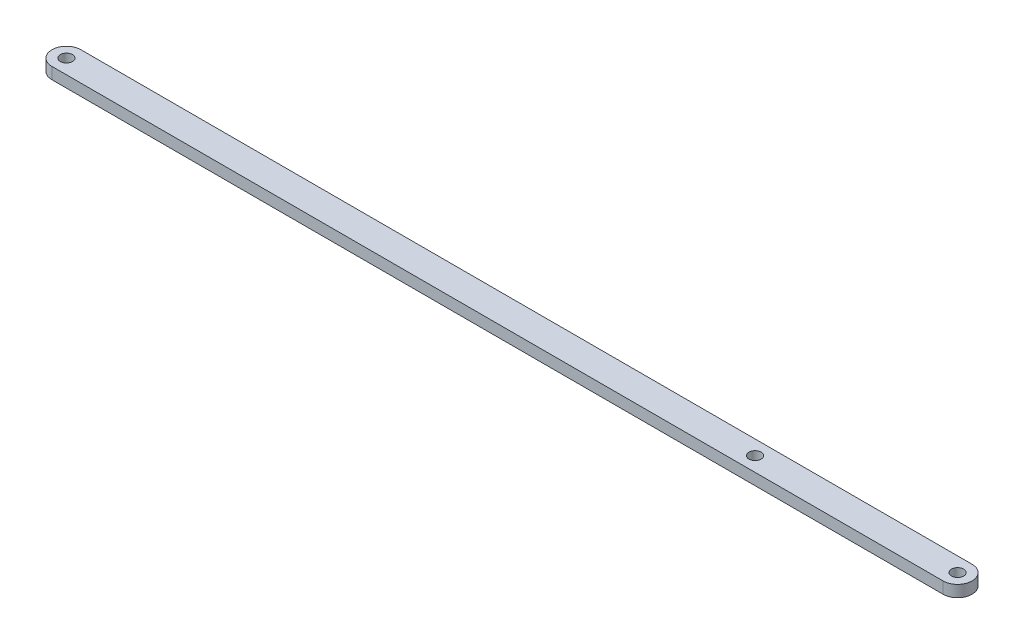
SolidWorks part; units mm, degrees
ref_plane "Front Plane" through (0, 0, 0) normal (0, 0, 1) x (1, 0, 0)
ref_plane "Top Plane" through (0, 0, 0) normal (0, 1, 0) x (1, 0, 0)
ref_plane "Right Plane" through (0, 0, 0) normal (1, 0, 0) x (0, 0, -1)
sketch "Sketch1" plane through (0, 0, 0) normal (0, 1, 0) x (1, 0, 0)
  line L0 (0, 0) -> (154, 0) construction
  line L1 (0, 2.5) -> (154, 2.5)
  line L2 (0, -2.5) -> (154, -2.5)
  arc A0 (0, 2.5) -> (0, -2.5) centre (0, 0) ccw
  arc A1 (154, -2.5) -> (154, 2.5) centre (154, 0) ccw
  circle A2 centre (0, 0) radius 1.05
  circle A3 centre (154, 0) radius 1.05
  circle A5 centre (119, 0) radius 1.05
  point P3 (77, 0)
  dimension "D1" = 2.5
  dimension "D3" = 2.1
  dimension "D4" = 2.1
  dimension "D5" = 2.1
  dimension "D2" = 154
  dimension "D6" = 35
extrude "Boss-Extrude1" add sketch "Sketch1" along normal blind 2
